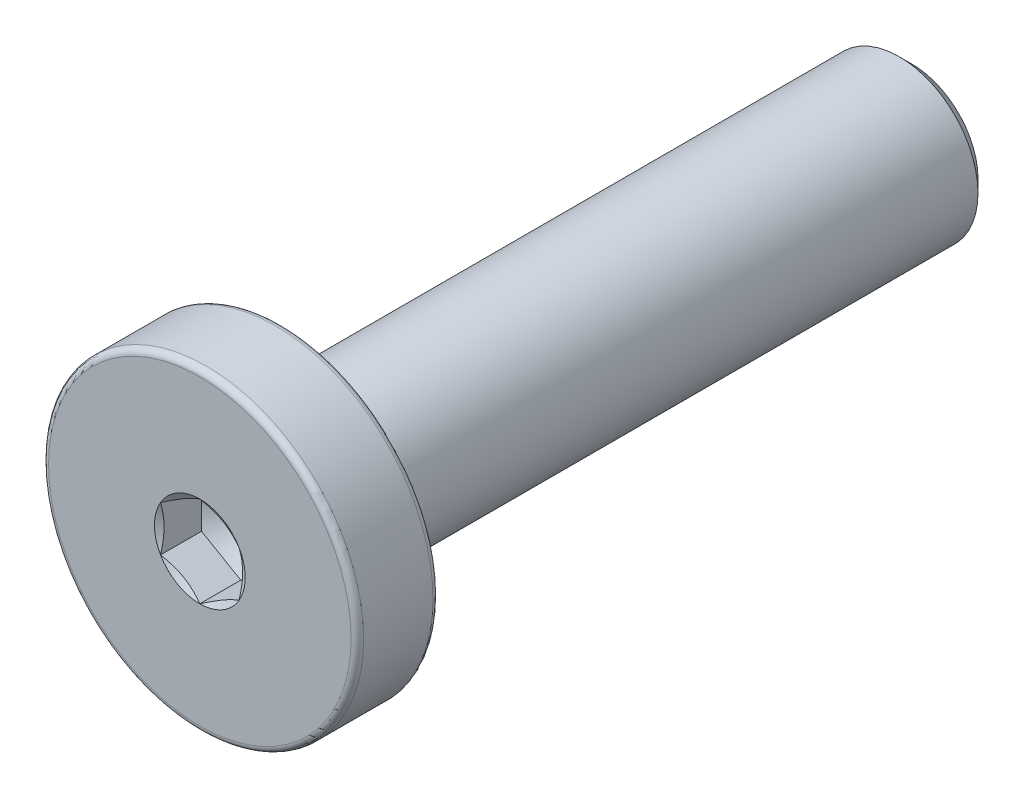
SolidWorks part; units mm, degrees
ref_plane "Front Plane" through (0, 0, 0) normal (0, 0, 1) x (1, 0, 0)
ref_plane "Top Plane" through (0, 0, 0) normal (0, 1, 0) x (1, 0, 0)
ref_plane "Right Plane" through (0, 0, 0) normal (1, 0, 0) x (0, 0, -1)
sketch "Sketch2" plane through (0, 0, 0) normal (1, 0, 0) x (0, 0, -1)
  line L0 (-1.3, 0) -> (-1.3, 53.302) construction
  line L1 (-1.3, 0) -> (56.272, 0) construction
  line L2 (-1.3, 0) -> (-1.3, 2.5)
  line L3 (-1.3, 2.5) -> (0, 2.5)
  line L4 (0, 2.5) -> (0, 1.25)
  line L5 (0, 1.25) -> (10, 1.25)
  line L6 (10, 1.25) -> (10, 0)
  line L7 (10, 0) -> (-1.3, 0)
  line L8 (0, 0) -> (0, 9.2664) construction
  line L9 (-0.272, 0) -> (18.2846, 0) construction
  dimension "D1" = 5
  dimension "D2" = 2.5
  dimension "D3" = 1.3
  dimension "D4" = 10
revolve "Revolve1" add sketch "Sketch2" angle 360 about L1
sketch "Sketch3" plane through (0, 0, 1.3) normal (0, 0, 1) x (1, 0, 0)
  line L0 (0, 0.72) -> (-0.6235, 0.36)
  line L1 (-0.6235, 0.36) -> (-0.6235, -0.36)
  line L2 (-0.6235, -0.36) -> (0, -0.72)
  line L3 (0, -0.72) -> (0.6235, -0.36)
  line L4 (0.6235, -0.36) -> (0.6235, 0.36)
  line L5 (0.6235, 0.36) -> (0, 0.72)
  circle A0 centre (0, 0) radius 0.72 construction
  dimension "D1" = 1.44
extrude "Cut-Extrude1" cut sketch "Sketch3" against normal blind 0.65
fillet "Fillet1" radius 0.1 2 edges at (2.5, 0, 0) (2.5, 0, 1.3)
chamfer "Chamfer1" distance 0.2 angle 45 1 edges at (1.25, 0, -10)
sketch "Sketch4" plane through (0, 0, 0) normal (1, 0, 0) x (0, 0, -1)
  line L0 (-0.65, -0.36) -> (-0.65, 0.36) construction
  line L1 (-0.65, 0.36) -> (-0.65, 0.72) construction
  line L2 (-0.65, 0.72) -> (-1.3, 0.72) construction
  line L3 (-0.65, -0.36) -> (-0.65, 0.36) construction
  line L4 (-0.65, 0.36) -> (-0.65, 0.72) construction
  line L5 (-0.65, 0.72) -> (-1.3, 0.72) construction
  line L6 (0, 0) -> (2.7271, 0) construction
  line L7 (-0.65, 0.72) -> (-0.2174, 0)
  line L8 (-0.2174, 0) -> (-0.65, 0)
  line L9 (-0.65, 0) -> (-0.65, 0.72)
  line L10 (-1.3, 0.72) -> (-1.3, 0.57)
  line L11 (-1.3, 2.4) -> (-1.3, -2.4) construction
  line L13 (-1.3, 0.57) -> (-1.2134, 0.57)
  line L14 (-1.2134, 0.57) -> (-1.3, 0.72)
  dimension "D1" = 30
  dimension "D2" = 0.15
  dimension "D3" = 59
revolve "Cut-Revolve1" cut sketch "Sketch4" angle 360 about L6
